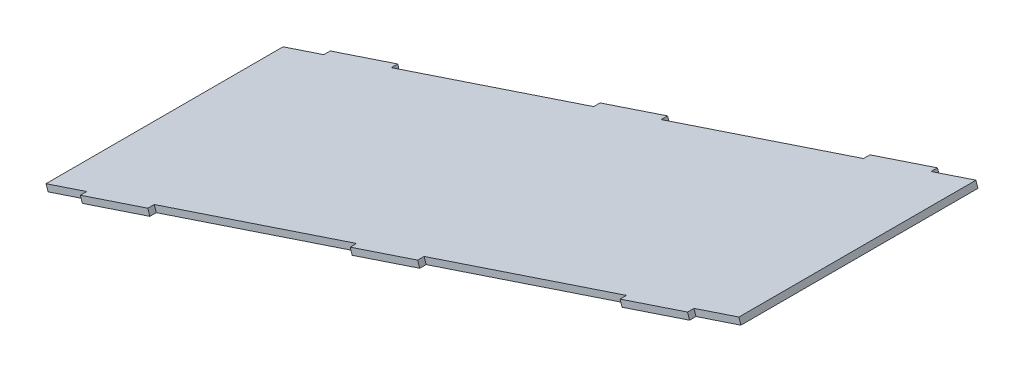
SolidWorks part; units mm, degrees
ref_plane "Front Plane" through (0, 0, 0) normal (0, 0, 1) x (1, 0, 0)
ref_plane "Top Plane" through (0, 0, 0) normal (0, 1, 0) x (1, 0, 0)
ref_plane "Right Plane" through (0, 0, 0) normal (1, 0, 0) x (0, 0, -1)
sketch "Sketch1" plane through (0, 0, 0) normal (0, 0, 1) x (1, 0, 0)
  line L0 (-300, 0) -> (-299.1462, -2.5614)
  line L1 (-299.1462, -2.5614) -> (0.8538, 97.4386)
  line L2 (0.8538, 97.4386) -> (0, 100)
  line L3 (0, 100) -> (-300, 0)
  point P2 (0, 0)
  point P5 (0, 0)
  dimension "D1" = 2.7
extrude "Boss-Extrude1" add sketch "Sketch1" along normal blind 50
sketch "Sketch2" plane through (-30, 90, 0) normal (-0.3162, 0.9487, 0) x (0.9487, 0.3162, 0)
  line L0 (11.6228, 0) -> (11.6228, 2.7)
  line L1 (31.6228, 0) -> (-284.605, 0) construction
  line L2 (11.6228, 2.7) -> (-18.3772, 2.7)
  line L3 (-18.3772, 2.7) -> (-18.3772, 0)
  line L4 (-18.3772, 0) -> (11.6228, 0)
  line L5 (31.6228, -50) -> (31.6228, 0) construction
  line L6 (-108.3772, 0) -> (-108.3772, 2.7)
  line L7 (-108.3772, 2.7) -> (-138.3772, 2.7)
  line L8 (-138.3772, 2.7) -> (-138.3772, 0)
  line L9 (-138.3772, 0) -> (-108.3772, 0)
  line L10 (-228.3772, 0) -> (-228.3772, 2.7)
  line L11 (-228.3772, 2.7) -> (-258.3772, 2.7)
  line L12 (-258.3772, 2.7) -> (-258.3772, 0)
  line L13 (-258.3772, 0) -> (-228.3772, 0)
  point P8 (11.6228, 1.35)
  dimension "D1" = 30
  dimension "D2" = 20
  dimension "D3" = 3
extrude "Boss-Extrude2" add sketch "Sketch2" against normal up to surface (2.7 mm away) up to face at (-149.1462, 47.4386, 25)
ref_plane "Plane1" through (0, 0, 50) normal (0, 0, 1) x (1, 0, 0)
mirror "Mirror1" about plane through (0, 0, 50) normal (0, 0, 1) of "Boss-Extrude1"
mirror "Mirror2" about plane through (0, 0, 50) normal (0, 0, 1) of "Boss-Extrude2"
sketch "Sketch3" plane through (-30, 90, 0) normal (-0.3162, 0.9487, 0) x (0.9487, 0.3162, 0)
  line L0 (-284.605, -100) -> (-284.605, 0) construction
  line L1 (-284.605, 0) -> (-281.8615, 0)
  line L2 (-284.605, 0) -> (-284.605, -100)
  line L3 (-284.605, -100) -> (-281.8615, -100)
  line L4 (-281.8615, 0) -> (-281.8615, -100)
  line L5 (-258.3772, -100) -> (-284.605, -100) construction
  dimension "D1" = 2.7435
extrude "Cut-Extrude1" cut sketch "Sketch3" against normal blind 50
sketch "Sketch4" plane through (0, 0, 0) normal (0, 0, -1) x (-1, 0, 0)
  line L0 (296.5435, -1.6939) -> (297.1081, 0)
  line L1 (296.5435, -1.6939) -> (297.3973, 0.8676) construction
  line L2 (265.2117, 0) -> (300, 0) construction
  line L4 (296.5435, -1.6939) -> (274.2643, 5.7325) construction
  line L5 (299.1462, -2.5614) -> (-0.8538, 97.4386) construction
  line L6 (291.4619, 0) -> (296.5435, -1.6939)
  line L7 (291.4619, 0) -> (292.3157, 2.5614)
  line L8 (275.1182, 8.2939) -> (297.3973, 0.8676) construction
  line L9 (292.3157, 2.5614) -> (297.3973, 0.8676)
  line L10 (297.3973, 0.8676) -> (297.1081, 0)
  point P7 (0, 0)
  point P18 (291.4619, 0)
  point P19 (291.4619, 0)
extrude "Cut-Extrude2" cut sketch "Sketch4" against normal through all
sketch "Sketch5" plane through (-30, 90, 0) normal (-0.3162, 0.9487, 0) x (0.9487, 0.3162, 0)
  line L0 (-271.5195, 0) -> (-271.5195, -14.7404) construction
  line L1 (1.2649, 2.7) -> (-293.0803, 2.7) construction
  line L2 (-258.3772, 0) -> (-276.505, 0) construction
  line L6 (-276.505, 2.7) -> (-258.8772, 2.7) construction
  line L28 (-258.3772, 0) -> (-276.505, 0)
  line L29 (-276.505, 0) -> (-276.505, -100)
  line L30 (-276.505, -100) -> (-258.3772, -100)
  line L31 (-258.3772, -100) -> (-258.3772, -102.7)
  line L32 (-258.3772, -102.7) -> (-228.3772, -102.7)
  line L33 (-228.3772, -102.7) -> (-228.3772, -100)
  line L34 (-228.3772, -100) -> (-138.3772, -100)
  line L35 (-138.3772, -100) -> (-138.3772, -102.7)
  line L36 (-138.3772, -102.7) -> (-108.3772, -102.7)
  line L37 (-108.3772, -102.7) -> (-108.3772, -100)
  line L38 (-108.3772, -100) -> (-18.3772, -100)
  line L39 (-18.3772, -100) -> (-18.3772, -102.7)
  line L40 (-18.3772, -102.7) -> (11.6228, -102.7)
  line L41 (11.6228, -102.7) -> (11.6228, -100)
  line L42 (11.6228, -100) -> (31.6228, -100)
  line L43 (31.6228, -100) -> (31.6228, 0)
  line L44 (31.6228, 0) -> (11.6228, 0)
  line L45 (11.6228, 0) -> (11.6228, 2.7)
  line L46 (11.6228, 2.7) -> (-18.3772, 2.7)
  line L47 (-18.3772, 2.7) -> (-18.3772, 0)
  line L48 (-18.3772, 0) -> (-108.3772, 0)
  line L49 (-108.3772, 0) -> (-108.3772, 2.7)
  line L50 (-108.3772, 2.7) -> (-138.3772, 2.7)
  line L51 (-138.3772, 2.7) -> (-138.3772, 0)
  line L52 (-138.3772, 0) -> (-228.3772, 0)
  line L53 (-228.3772, 0) -> (-228.3772, 2.7)
  line L54 (-228.3772, 2.7) -> (-258.3772, 2.7)
  line L55 (-258.3772, 2.7) -> (-258.3772, 0)
  line L56 (-258.3772, 0) -> (-276.505, 0)
  line L57 (-276.505, 0) -> (-276.505, -100)
  line L58 (-276.505, -100) -> (-258.3772, -100)
  line L59 (-258.3772, -100) -> (-258.3772, -102.7)
  line L60 (-258.3772, -102.7) -> (-228.3772, -102.7)
  line L61 (-228.3772, -102.7) -> (-228.3772, -100)
  line L62 (-228.3772, -100) -> (-138.3772, -100)
  line L63 (-138.3772, -100) -> (-138.3772, -102.7)
  line L64 (-138.3772, -102.7) -> (-108.3772, -102.7)
  line L65 (-108.3772, -102.7) -> (-108.3772, -100)
  line L66 (-108.3772, -100) -> (-18.3772, -100)
  line L67 (-18.3772, -100) -> (-18.3772, -102.7)
  line L68 (-18.3772, -102.7) -> (11.6228, -102.7)
  line L69 (11.6228, -102.7) -> (11.6228, -100)
  line L70 (11.6228, -100) -> (31.6228, -100)
  line L71 (31.6228, -100) -> (31.6228, 0)
  line L72 (31.6228, 0) -> (11.6228, 0)
  line L73 (11.6228, 0) -> (11.6228, 2.7)
  line L74 (11.6228, 2.7) -> (-18.3772, 2.7)
  line L75 (-18.3772, 2.7) -> (-18.3772, 0)
  line L76 (-18.3772, 0) -> (-108.3772, 0)
  line L77 (-108.3772, 0) -> (-108.3772, 2.7)
  line L78 (-108.3772, 2.7) -> (-138.3772, 2.7)
  line L79 (-138.3772, 2.7) -> (-138.3772, 0)
  line L80 (-138.3772, 0) -> (-228.3772, 0)
  line L81 (-228.3772, 0) -> (-228.3772, 2.7)
  line L82 (-228.3772, 2.7) -> (-258.3772, 2.7)
  line L83 (-258.3772, 2.7) -> (-258.3772, 0)
  point P6 (-271.6239, 2.7)
  point P8 (-271.6239, 2.7)
  dimension "D1" = 0
